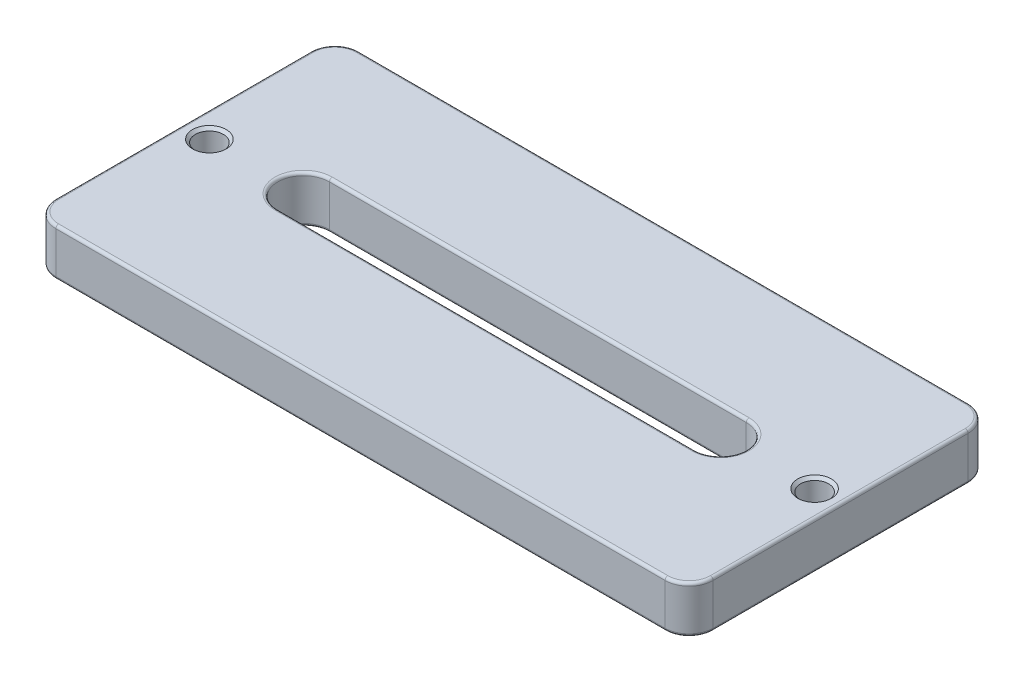
SolidWorks part; units mm, degrees
ref_plane "Front" through (0, 0, 0) normal (0, 0, 1) x (1, 0, 0)
ref_plane "Top" through (0, 0, 0) normal (0, 1, 0) x (1, 0, 0)
ref_plane "Right" through (0, 0, 0) normal (1, 0, 0) x (0, 0, -1)
sketch "Sketch1" plane through (0, 0, 0) normal (0, 1, 0) x (1, 0, 0)
  line L0 (0, 4.8014) -> (0, -3.1451) construction
  line L1 (-41, 18.9) -> (41, 18.9)
  line L3 (-41, -18.9) -> (41, -18.9)
  line L5 (-4.3063, 0) -> (6.6584, 0) construction
  line L6 (-25.9975, 3.225) -> (-13.6235, 3.225)
  line L7 (-25.9975, -3.225) -> (-13.6235, -3.225)
  line L8 (13.6235, 3.225) -> (25.9975, 3.225)
  line L9 (13.6235, -3.225) -> (25.9975, -3.225)
  line L18 (41, 18.9) -> (41, -18.9)
  line L19 (-41, -18.9) -> (-41, 18.9)
  line L20 (-13.6235, 3.225) -> (13.6235, 3.225)
  line L21 (-13.6235, -3.225) -> (13.6235, -3.225)
  arc A1 (25.9975, -3.225) -> (25.9975, 3.225) centre (25.9975, 0) ccw
  arc A2 (-25.9975, 3.225) -> (-25.9975, -3.225) centre (-25.9975, 0) ccw
  circle A10 centre (28, -12.4) radius 1.75 construction
  circle A11 centre (28, 12.4) radius 1.75 construction
  circle A12 centre (-28, 12.4) radius 1.75 construction
  circle A13 centre (-28, -12.4) radius 1.75 construction
  circle A14 centre (37.75, 0) radius 1.75
  circle A15 centre (-37.75, 0) radius 1.75
  circle A16 centre (0, 0) radius 6.3672 construction
  point P10 (0, 14)
  point P12 (-29.2225, 0)
  dimension "D4" = 6.45
  dimension "D5" = 3.5
  dimension "D11" = 3.5
  dimension "D6" = 3.5
  dimension "D1" = 82
  dimension "D2" = 37.8
  dimension "D7" = 3.25
  dimension "D8" = 55.22
  dimension "D12" = 13
  dimension "D13" = 6.5
extrude "Boss-Extrude1" add sketch "Sketch1" along normal blind 5.85
fillet "Fillet2" radius 3 4 edges at (41, 2.925, -18.9) (41, 2.925, 18.9) (-41, 2.925, -18.9) (-41, 2.925, 18.9)
fillet "Fillet3" radius 0.35 24 edges at (29.2225, 5.85, 0) (0, 5.85, 3.225) (-29.2225, 5.85, 0) (29.2225, 0, 0) (0, 0, 3.225) (-29.2225, 0, 0) (0, 5.85, -3.225) (0, 0, -3.225) (40.1213, 0, -18.0213) (41, 0, 0) (40.1213, 0, 18.0213) (0, 0, 18.9) (-40.1213, 0, 18.0213) (-41, 0, 0) (-40.1213, 0, -18.0213) (40.1213, 5.85, -18.0213) (41, 5.85, 0) (40.1213, 5.85, 18.0213) (0, 5.85, 18.9) (-40.1213, 5.85, 18.0213) (-41, 5.85, 0) (-40.1213, 5.85, -18.0213) (0, 0, -18.9) (0, 5.85, -18.9)
chamfer "Chamfer1" distance 0.35 angle 45 4 edges at (-37.75, 0, 1.75) (-37.75, 5.85, 1.75) (37.75, 0, 1.75) (37.75, 5.85, 1.75)
equation "\"D1@Boss-Extrude1\"= 6.35mm - 2*0.15 - 0.2"
